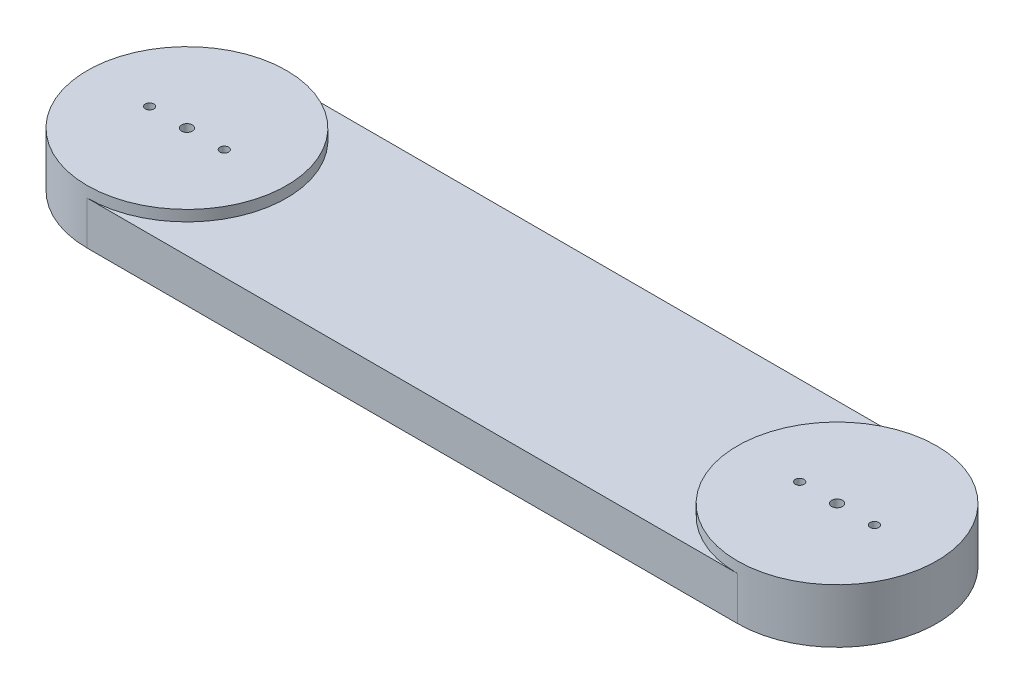
SolidWorks part; units mm, degrees
ref_plane "前视基准面" through (0, 0, 0) normal (0, 0, 1) x (1, 0, 0)
ref_plane "上视基准面" through (0, 0, 0) normal (0, 1, 0) x (1, 0, 0)
ref_plane "右视基准面" through (0, 0, 0) normal (1, 0, 0) x (0, 0, -1)
other "Configuration Table"
sketch "草图1" plane through (0, 0, 0) normal (0, 1, 0) x (1, 0, 0)
  line L1 (-150, -46) -> (150, -46)
  line L2 (-150, -46) -> (-150, 46)
  line L3 (-150, 46) -> (150, 46)
  line L4 (150, -46) -> (150, 46)
  line L5 (-150, -46) -> (150, 46) construction
  line L6 (-150, 46) -> (150, -46) construction
  point P0 (0, 0)
  dimension "D1" = 300
  dimension "D2" = 92
extrude "凸台-拉伸1" add sketch "草图1" along normal blind 20
sketch "草图2" plane through (0, 0, 0) normal (0, -1, 0) x (1, 0, 0)
  line L0 (-150, -46) -> (-150, 46) construction
  line L1 (150, 46) -> (150, -46) construction
  circle A0 centre (-150, 0) radius 46
  circle A1 centre (150, 0) radius 46
extrude "凸台-拉伸2" add sketch "草图2" against normal blind 25
sketch "草图3" plane through (0, 25, 0) normal (0, 1, 0) x (1, 0, 0)
  line L0 (150, 46) -> (150, -46) construction
  line L1 (150, 46) -> (-150, 46) construction
  line L2 (104, 0) -> (196, 0) construction
  circle A0 centre (150, 0) radius 46 construction
  arc A1 (150, 46) -> (150, -46) centre (150, 0) ccw construction
  circle A2 centre (150, 0) radius 2.5
  circle A3 centre (167.25, 0) radius 2
  circle A4 centre (132.75, 0) radius 2
  dimension "D1" = 34.5
extrude "切除-拉伸1" cut sketch "草图3" against normal through all
sketch "草图4" plane through (0, 25, 0) normal (0, 1, 0) x (1, 0, 0)
  line L0 (-150, 46) -> (-150, -46) construction
  line L1 (-196, 0) -> (-104, 0) construction
  circle A0 centre (-150, 0) radius 46 construction
  circle A1 centre (-150, 0) radius 2.5
  circle A2 centre (-132.75, 0) radius 2
  circle A3 centre (-167.25, 0) radius 2
  dimension "D1" = 34.5
extrude "切除-拉伸2" cut sketch "草图4" against normal through all
sketch "草图5" plane through (0, 0, 0) normal (0, -1, 0) x (1, 0, 0)
  circle A0 centre (-150, 0) radius 29.5
extrude "切除-拉伸3" cut sketch "草图5" against normal blind 6.6
